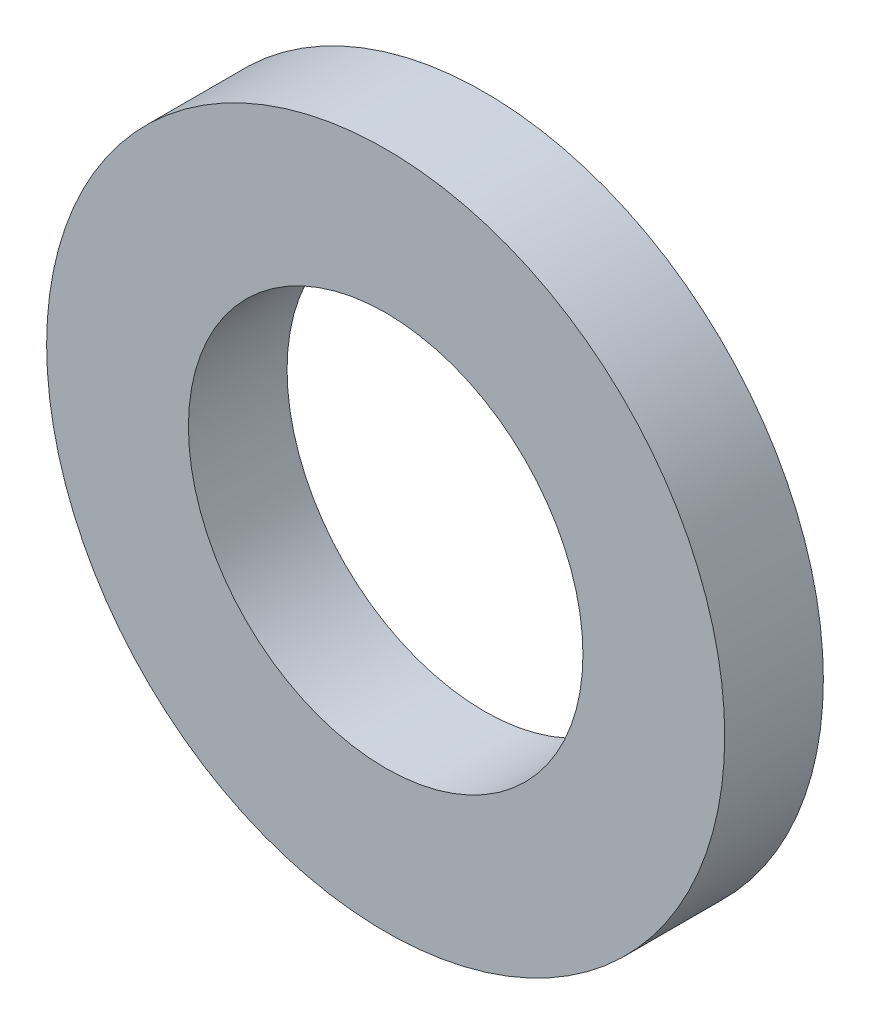
SolidWorks part; units mm, degrees
ref_plane "前视基准面" through (0, 0, 0) normal (0, 0, 1) x (1, 0, 0)
ref_plane "上视基准面" through (0, 0, 0) normal (0, 1, 0) x (1, 0, 0)
ref_plane "右视基准面" through (0, 0, 0) normal (1, 0, 0) x (0, 0, -1)
sketch "草图1" plane through (0, 0, 0) normal (0, 0, 1) x (1, 0, 0)
  circle A0 centre (0, 0) radius 5.5
  dimension "D1" = 11
extrude "拉伸1" add sketch "草图1" along normal blind 1.6
sketch "草图2" plane through (0, 0, 1.6) normal (0, 0, 1) x (1, 0, 0)
  circle A0 centre (0, 0) radius 3.2
  dimension "D1" = 6.4
extrude "切除-拉伸1" cut sketch "草图2" against normal through all
